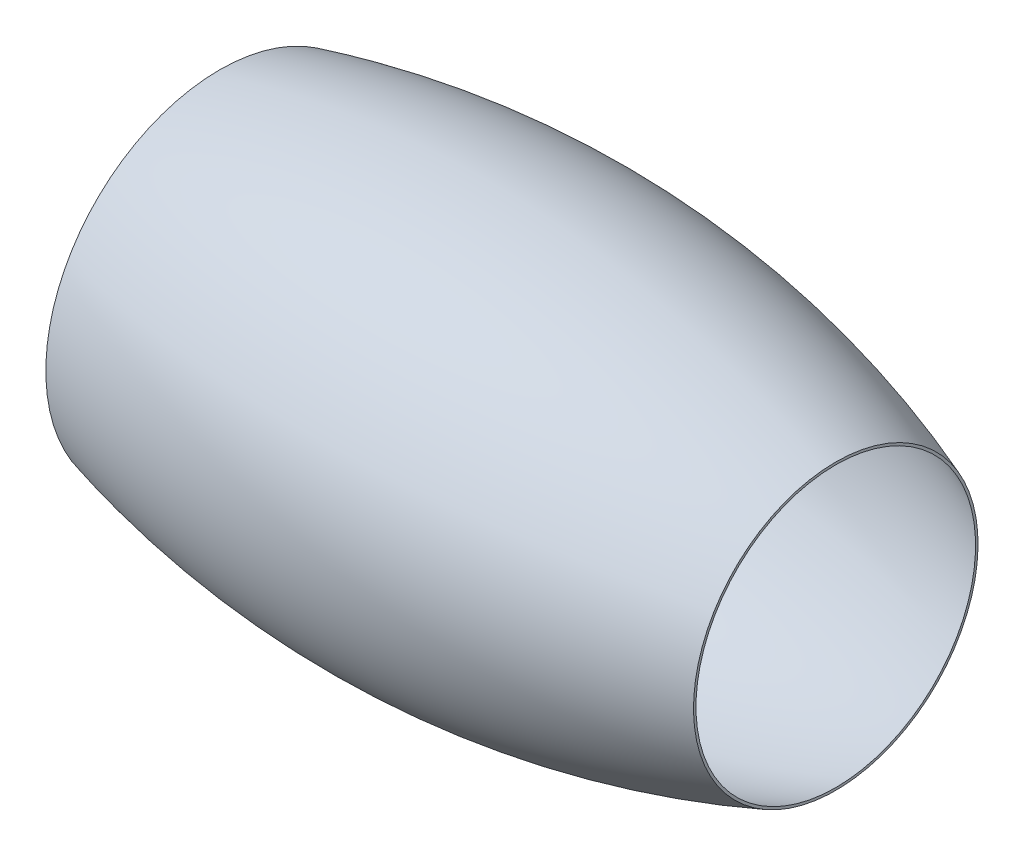
SolidWorks part; units mm, degrees
ref_plane "Front Plane" through (0, 0, 0) normal (0, 0, 1) x (1, 0, 0)
ref_plane "Top Plane" through (0, 0, 0) normal (0, 1, 0) x (1, 0, 0)
ref_plane "Right Plane" through (0, 0, 0) normal (1, 0, 0) x (0, 0, -1)
sketch "Sketch1" plane through (0, 0, 0) normal (0, 0, 1) x (1, 0, 0)
  line L0 (1000, 0) -> (-1000, 0) construction
  line L1 (0, 0) -> (0, 260) construction
  line L2 (994.5773, 227) -> (994.5773, 231)
  line L3 (994.5773, 0) -> (994.5773, 227) construction
  line L4 (0, 260) -> (0, 303.985) construction
  line L5 (-5.0546, 279.2989) -> (-4.6745, 277.8479)
  line L6 (-5.8198, 282.1952) -> (-5.4377, 280.7447)
  line L9 (-5.4377, 280.7447) -> (-13.5189, 311.4195) construction
  line L12 (0, 240.0501) -> (0, 237.0545)
  line L13 (-4.6745, 277.8479) -> (-1.7724, 278.608)
  line L14 (-5.4377, 280.7447) -> (-2.5367, 281.509)
  line L15 (-2.5367, 281.509) -> (-1.7724, 278.608)
  line L16 (-4.6745, 277.8479) -> (0, 260) construction
  arc A0 (-5.8198, 282.1952) -> (0, 237.0545) centre (0, 260) ccw
  arc A1 (-5.0546, 279.2989) -> (0, 240.0501) centre (0, 260) ccw
  arc A2 (-5.8198, 282.1952) -> (994.5773, 231) centre (414.0294, -1313.4948) cw
  arc A3 (-1.7724, 278.608) -> (994.5773, 227) centre (415.263, -1313.6852) cw
  point P4 (0, 0)
  dimension "D1" = 1.5
  dimension "D2" = 260
  dimension "D4" = 4
  dimension "D10" = 1650
  dimension "D11" = 1646
  dimension "D3" = 227
  dimension "D5" = 995
  dimension "D6" = 1.5
  dimension "D7" = 3
  dimension "D8" = 3
  dimension "D9" = 3
revolve "Revolve1" add sketch "Sketch1" angle 360 about L0
